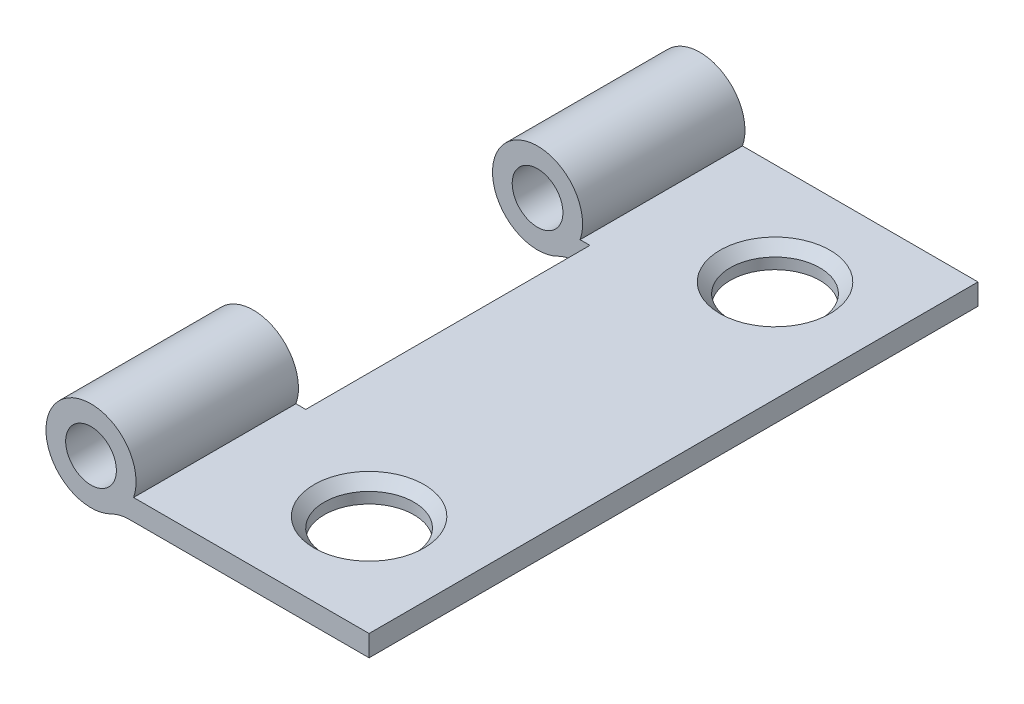
SolidWorks part; units mm, degrees
material "Chrome Stainless Steel"
ref_plane "Front Plane" through (0, 0, 0) normal (0, 0, 1) x (1, 0, 0)
ref_plane "Top Plane" through (0, 0, 0) normal (0, 1, 0) x (1, 0, 0)
ref_plane "Right Plane" through (0, 0, 0) normal (1, 0, 0) x (0, 0, -1)
sketch "Sketch2" plane through (0, 0, 0) normal (0, 0, 1) x (1, 0, 0)
  circle A0 centre (0, 0) radius 1.5875
  circle A1 centre (0, 0) radius 2.8194
  dimension "D1" = 5.6388
  dimension "D2" = 3.175
extrude "Boss-Extrude1" add sketch "Sketch2" along normal mid plane 38.1
sketch "Sketch3" plane through (0, 0, 0) normal (0, 0, 1) x (1, 0, 0)
  line L1 (2.6626, -0.9271) -> (17.399, -0.9271)
  line L3 (1.7018, -2.2479) -> (17.399, -2.2479)
  line L4 (17.399, -0.9271) -> (17.399, -2.2479)
  circle A1 centre (0, 0) radius 2.8194 construction
  arc A2 (1.7018, -2.2479) -> (2.6626, -0.9271) centre (0, 0) ccw
  circle A3 centre (0, 0) radius 1.5875 construction
  point P0 (17.399, -1.5875)
  point P2 (0, -1.5875)
  point P7 (2.8194, 0)
  point P8 (17.2876, -1.8526)
  point P14 (0, 0)
  point P15 (0, 0)
  dimension "D2" = 14.5796
  dimension "D1" = 1.3208
extrude "Boss-Extrude2" add sketch "Sketch3" along normal up to surface and the other way up to surface up to face at (2.8194, 0, 19.05) other way up to face at (2.8194, 0, -19.05)
fillet "Fillet1" radius 2.54 1 edges at (1.7018, -2.2479, 0)
sketch "Sketch4" plane through (0, 0, 0) normal (0, 0, 1) x (1, 0, 0)
  line L0 (17.399, -2.2479) -> (17.399, -0.9271) construction
  line L1 (-3.2766, -3.2766) -> (3.2766, -3.2766)
  line L2 (-3.2766, -3.2766) -> (-3.2766, 3.2766)
  line L3 (-3.2766, 3.2766) -> (3.2766, 3.2766)
  line L4 (3.2766, -3.2766) -> (3.2766, 3.2766)
  line L5 (-3.2766, -3.2766) -> (3.2766, 3.2766) construction
  line L6 (-3.2766, 3.2766) -> (3.2766, -3.2766) construction
  point P0 (0, 0)
  dimension "D1" = 14.1224
extrude "Cut-Extrude1" cut sketch "Sketch4" against normal mid plane 17.78
hole_wizard "#10 Clearance Hole1" positions "Sketch5" profile "Sketch6" hole size "#10" standard "ANSI Inch" end condition through all
sketch "Sketch5" plane through (0, -0.9271, 0) normal (0, 1, 0) x (1, 0, 0)
  line L0 (11.049, 12.7) -> (11.049, -12.7) construction
  line L2 (2.6626, 19.05) -> (17.399, 19.05) construction
  line L3 (17.399, -19.05) -> (17.399, 19.05) construction
  point P0 (11.049, 12.7)
  point P2 (11.049, -12.7)
  point P9 (11.049, 0)
  dimension "D1" = 6.35
  dimension "D2" = 6.35
sketch "Sketch6" plane through (11.049, -0.9271, -12.7) normal (1, 0, 0) x (0, 0, 1)
  line L0 (0, 0) -> (0, 1.8923)
  line L1 (0, 1.8923) -> (2.8067, 1.8923)
  line L2 (2.8067, 1.8923) -> (2.8067, 0.635)
  line L3 (2.8067, 0.635) -> (3.4417, 0)
  line L5 (3.4417, 0) -> (0, 0)
  line L6 (-2.8067, 0.635) -> (-3.4417, 0) construction
  line L11 (0, -6.35) -> (0, 107.95) construction
  dimension "Thru Hole Dia." = 5.6134
  dimension "Thru Hole Depth" = 1.8923
  dimension "Near C'Sink Dia." = 6.8834
  dimension "Near C'Sink Angle" = 90
